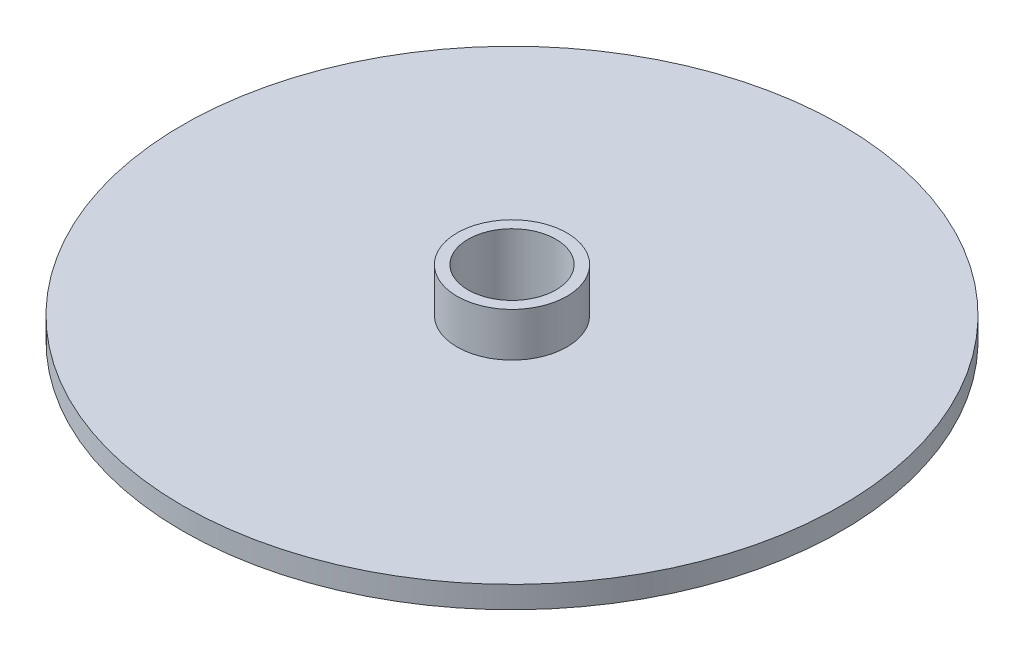
SolidWorks part; units mm, degrees
material "Copper"
ref_plane "Front Plane" through (0, 0, 0) normal (0, 0, 1) x (1, 0, 0)
ref_plane "Top Plane" through (0, 0, 0) normal (0, 1, 0) x (1, 0, 0)
ref_plane "Right Plane" through (0, 0, 0) normal (1, 0, 0) x (0, 0, -1)
sketch "Sketch1" plane through (0, 0, 0) normal (0, 1, 0) x (1, 0, 0)
  circle A0 centre (0, 0) radius 150
  circle A1 centre (0, 0) radius 25
  circle A2 centre (0, 0) radius 20
  point P3 (-150, 0)
  point P6 (20, 0)
  point P9 (-25, 0)
  dimension "D2" = 25
  dimension "D3" = 20
  dimension "D1" = 150
extrude "Boss-Extrude4" add sketch "Sketch1" along normal blind 10 contours A0 A1 | A1 A2
sketch "Sketch2" plane through (0, 10, 0) normal (0, 1, 0) x (1, 0, 0)
  circle A0 centre (0, 0) radius 25
  circle A1 centre (0, 0) radius 20
extrude "Boss-Extrude6" add sketch "Sketch2" along normal blind 20
